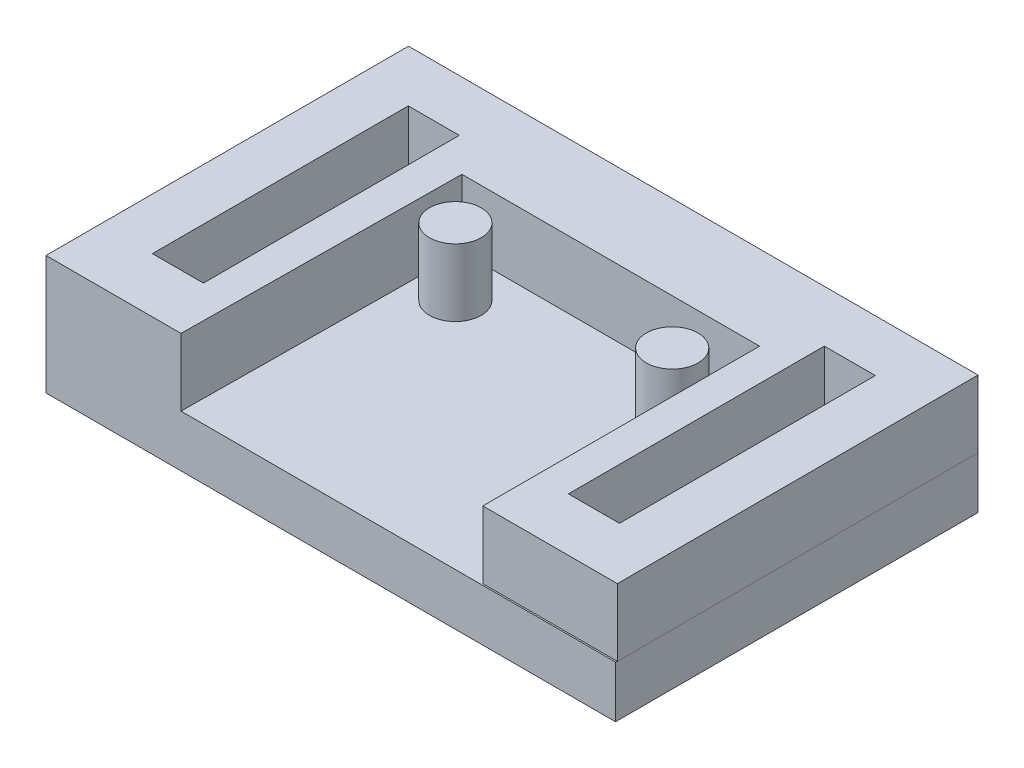
SolidWorks part; units mm, degrees
ref_plane "Front Plane" through (0, 0, 0) normal (0, 0, 1) x (1, 0, 0)
ref_plane "Top Plane" through (0, 0, 0) normal (0, 1, 0) x (1, 0, 0)
ref_plane "Right Plane" through (0, 0, 0) normal (1, 0, 0) x (0, 0, -1)
sketch "Sketch1" plane through (0, 0, 0) normal (0, 1, 0) x (1, 0, 0)
  line L0 (-13.97, 0) -> (-10.2049, 0) construction
  line L1 (-13.97, -8.89) -> (13.97, -8.89)
  line L2 (-13.97, -8.89) -> (-13.97, 8.89)
  line L3 (-13.97, 8.89) -> (13.97, 8.89)
  line L4 (13.97, -8.89) -> (13.97, 8.89)
  line L5 (-13.97, -8.89) -> (13.97, 8.89) construction
  line L6 (-13.97, 8.89) -> (13.97, -8.89) construction
  line L7 (0, -1000) -> (0, 49000) construction
  line L8 (-8.9349, -6.35) -> (-11.4749, -6.35)
  line L9 (-8.9349, -6.35) -> (-8.9349, 6.35)
  line L10 (-8.9349, 6.35) -> (-11.4749, 6.35)
  line L11 (-11.4749, -6.35) -> (-11.4749, 6.35)
  line L12 (-8.9349, -6.35) -> (-11.4749, 6.35) construction
  line L13 (-8.9349, 6.35) -> (-11.4749, -6.35) construction
  line L14 (8.9349, 6.35) -> (11.4749, 6.35)
  line L15 (11.4749, -6.35) -> (11.4749, 6.35)
  line L16 (8.9349, -6.35) -> (11.4749, -6.35)
  line L17 (8.9349, -6.35) -> (8.9349, 6.35)
  point P0 (0, 0)
  dimension "D1" = 17.78
  dimension "D2" = 27.94
  dimension "D3" = 12.7
  dimension "D4" = 2.54
extrude "Boss-Extrude2" add sketch "Sketch1" along normal blind 2.54
sketch "Sketch3" plane through (0, 2.54, 0) normal (0, 1, 0) x (1, 0, 0)
  line L0 (0, 8.89) -> (0, 2.54) construction
  line L1 (13.97, 8.89) -> (-13.97, 8.89) construction
  line L2 (5.3189, 2.54) -> (-5.3189, 2.54) construction
  circle A0 centre (-5.3189, 2.54) radius 1.27
  circle A1 centre (5.3189, 2.54) radius 1.27
extrude "Boss-Extrude3" add sketch "Sketch3" along normal blind 3.302
sketch3d "3DSketch2" plane through (0, 0, 0) normal (0, 0, 1) x (1, 0, 0)
  dimension "D1" = 3.302
sketch "Sketch4" plane through (0, 5.842, 0) normal (0, 1, 0) x (1, 0, 0)
  line L0 (-13.9518, 0.0729) -> (-10.1867, 0.0729) construction
  line L1 (-13.9518, -8.8171) -> (13.9882, -8.8171)
  line L2 (-13.9518, -8.8171) -> (-13.9518, 8.9629)
  line L3 (-13.9518, 8.9629) -> (13.9882, 8.9629)
  line L4 (13.9882, -8.8171) -> (13.9882, 8.9629)
  line L5 (-13.9518, -8.8171) -> (13.9882, 8.9629) construction
  line L6 (-13.9518, 8.9629) -> (13.9882, -8.8171) construction
  line L7 (0.0182, -999.9271) -> (0.0182, 49000.0729) construction
  line L8 (-8.9167, -6.2771) -> (-11.4567, -6.2771)
  line L9 (-8.9167, -6.2771) -> (-8.9167, 6.4229)
  line L10 (-8.9167, 6.4229) -> (-11.4567, 6.4229)
  line L11 (-11.4567, -6.2771) -> (-11.4567, 6.4229)
  line L12 (-8.9167, -6.2771) -> (-11.4567, 6.4229) construction
  line L13 (-8.9167, 6.4229) -> (-11.4567, -6.2771) construction
  line L14 (8.9531, 6.4229) -> (11.4931, 6.4229)
  line L15 (11.4931, -6.2771) -> (11.4931, 6.4229)
  line L16 (8.9531, -6.2771) -> (11.4931, -6.2771)
  line L17 (8.9531, -6.2771) -> (8.9531, 6.4229)
  point P0 (0.0182, 0.0729)
  dimension "D1" = 17.78
  dimension "D2" = 27.94
  dimension "D3" = 12.7
  dimension "D4" = 2.54
sketch "Sketch6" plane through (0, 2.54, 0) normal (0, 1, 0) x (1, 0, 0)
  line L0 (0.0182, 8.9629) -> (0.0182, -1.9707) construction
  line L1 (-13.9518, 8.9629) -> (13.9882, 8.9629) construction
  line L2 (0.0182, -200999.9271) -> (0.0182, 249000.0729) construction
  line L3 (-13.9518, -8.8171) -> (13.9882, 8.9629) construction
  line L8 (-7.2156, 4.7603) -> (7.3842, 4.7603)
  line L9 (11.4749, 6.35) -> (8.9713, 6.35)
  line L10 (-13.97, -8.89) -> (-13.97, 8.89)
  line L11 (-13.97, 8.89) -> (13.97, 8.89)
  line L12 (13.97, 8.89) -> (13.9882, -8.8171)
  line L13 (13.9882, -8.8171) -> (7.3842, -8.8171)
  line L14 (-13.9518, -8.8171) -> (13.9882, -8.8171) construction
  line L15 (7.3842, -8.8171) -> (7.3842, 4.7603)
  line L16 (-7.2156, 4.7603) -> (-7.3478, -8.89)
  line L17 (-13.97, -8.89) -> (13.97, -8.89) construction
  line L18 (-7.3478, -8.89) -> (-13.97, -8.89)
  line L19 (-11.4385, -6.2042) -> (-8.9349, -6.2042)
  line L20 (-11.4385, -6.2042) -> (-11.4385, 6.35)
  line L21 (-11.4385, 6.35) -> (-8.9349, 6.35)
  line L22 (-8.9349, -6.2042) -> (-8.9349, 6.35)
  line L23 (-11.4385, -6.2042) -> (-8.9349, 6.35) construction
  line L24 (-11.4385, 6.35) -> (-8.9349, -6.2042) construction
  line L25 (8.9713, -6.2042) -> (8.9713, 6.35)
  line L26 (11.4749, -6.2042) -> (8.9713, -6.2042)
  line L27 (11.4749, -6.2042) -> (11.4749, 6.35)
  line L28 (11.4749, 6.35) -> (8.9713, -6.2042) construction
  line L29 (11.4749, -6.2042) -> (8.9713, 6.35) construction
  point P7 (-10.1867, 0.0729)
  point P35 (10.2231, 0.0729)
extrude "Boss-Extrude6" add sketch "Sketch6" along normal blind 3.302
